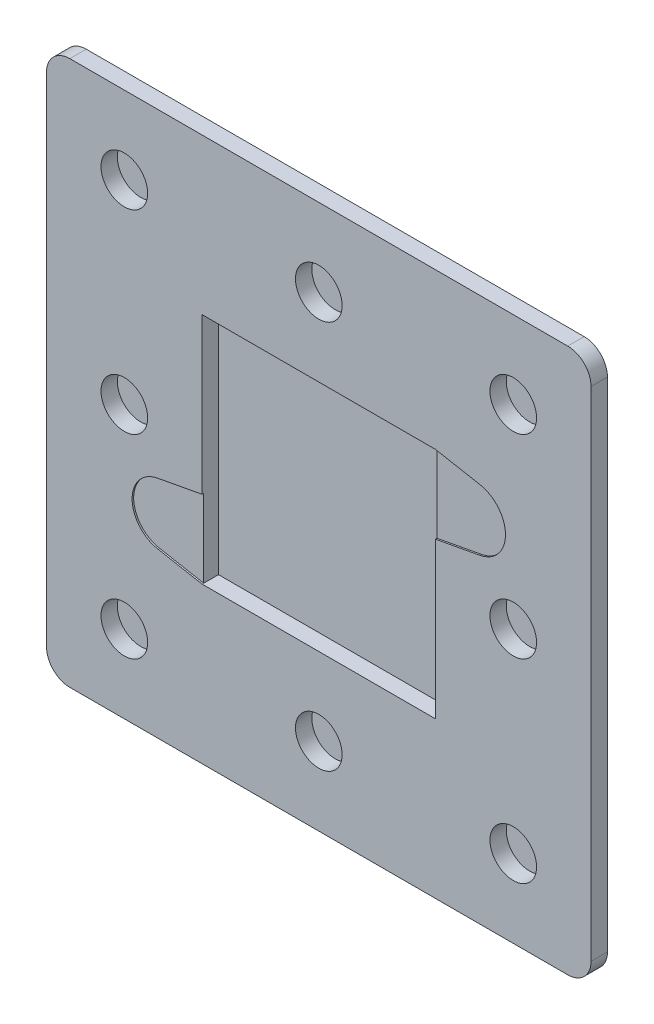
SolidWorks part; units mm, degrees
ref_plane "Front Plane" through (0, 0, 0) normal (0, 0, 1) x (1, 0, 0)
ref_plane "Top Plane" through (0, 0, 0) normal (0, 1, 0) x (1, 0, 0)
ref_plane "Right Plane" through (0, 0, 0) normal (1, 0, 0) x (0, 0, -1)
sketch "Sketch3" plane through (0, 0, 0) normal (0, 0, 1) x (1, 0, 0)
  line L1 (-35, -35) -> (35, -35)
  line L2 (-35, -35) -> (-35, 35)
  line L3 (-35, 35) -> (35, 35)
  line L4 (35, -35) -> (35, 35)
  line L5 (0, 35) -> (0, -35) construction
  line L6 (-35, 0) -> (35, 0) construction
  point P0 (0, 0)
  dimension "D1" = 70
  dimension "D2" = 70
extrude "Boss-Extrude1" add sketch "Sketch3" along normal blind 2.11
sketch "Sketch6" plane through (0, 0, 2.11) normal (0, 0, 1) x (1, 0, 0)
  line L9 (-15, -15) -> (15, -15)
  line L10 (-15, -15) -> (-15, 15)
  line L11 (-15, 15) -> (15, 15)
  line L12 (15, -15) -> (15, 15)
  line L13 (0, 15) -> (0, -15) construction
  line L14 (-15, 0) -> (15, 0) construction
  circle A0 centre (0, 25) radius 3
  circle A1 centre (25, 25) radius 3
  circle A2 centre (25, 0) radius 3
  circle A3 centre (25, -25) radius 3
  circle A4 centre (0, -25) radius 3
  circle A5 centre (-25, -25) radius 3
  circle A6 centre (-25, 0) radius 3
  circle A7 centre (-25, 25) radius 3
  point P0 (0, 0)
  point P12 (0, 0)
  point P13 (0, 0)
  dimension "D3" = 30
  dimension "D1" = 50
  dimension "D2" = 50
  dimension "D4" = 30
extrude "Cut-Extrude5" cut sketch "Sketch6" against normal blind 2.105
sketch "Sketch8" plane through (0, 0, 2.11) normal (0, 0, 1) x (1, 0, 0)
  line L0 (-15, 15) -> (-15, -15) construction
  line L1 (-35, -35) -> (35, -35) construction
  line L2 (35, 35) -> (-35, 35) construction
  line L3 (15, -15) -> (15, 15) construction
  line L5 (15, 5) -> (15, 15)
  line L6 (15, 15) -> (20.7324, 13.9324)
  line L7 (15, 5) -> (20.7324, 6.0676)
  line L8 (-15, -15) -> (-20.7324, -13.9324)
  line L9 (-15, -15) -> (-15, -5)
  line L10 (-15, -5) -> (-20.7324, -6.0676)
  arc A0 (20.7324, 6.0676) -> (20.7324, 13.9324) centre (20, 10) ccw
  arc A1 (-20.7324, -6.0676) -> (-20.7324, -13.9324) centre (-20, -10) ccw
  point P0 (0, 0)
  dimension "D3" = 25
  dimension "D5" = 8
  dimension "D6" = 8
  dimension "D1" = 5
  dimension "D2" = 25
  dimension "D4" = 5
extrude "Cut-Extrude7" cut sketch "Sketch8" against normal blind 0.2
fillet "Fillet1" radius 3 4 edges at (-35, -35, 1.055) (-35, 35, 1.055) (35, 35, 1.055) (35, -35, 1.055)
